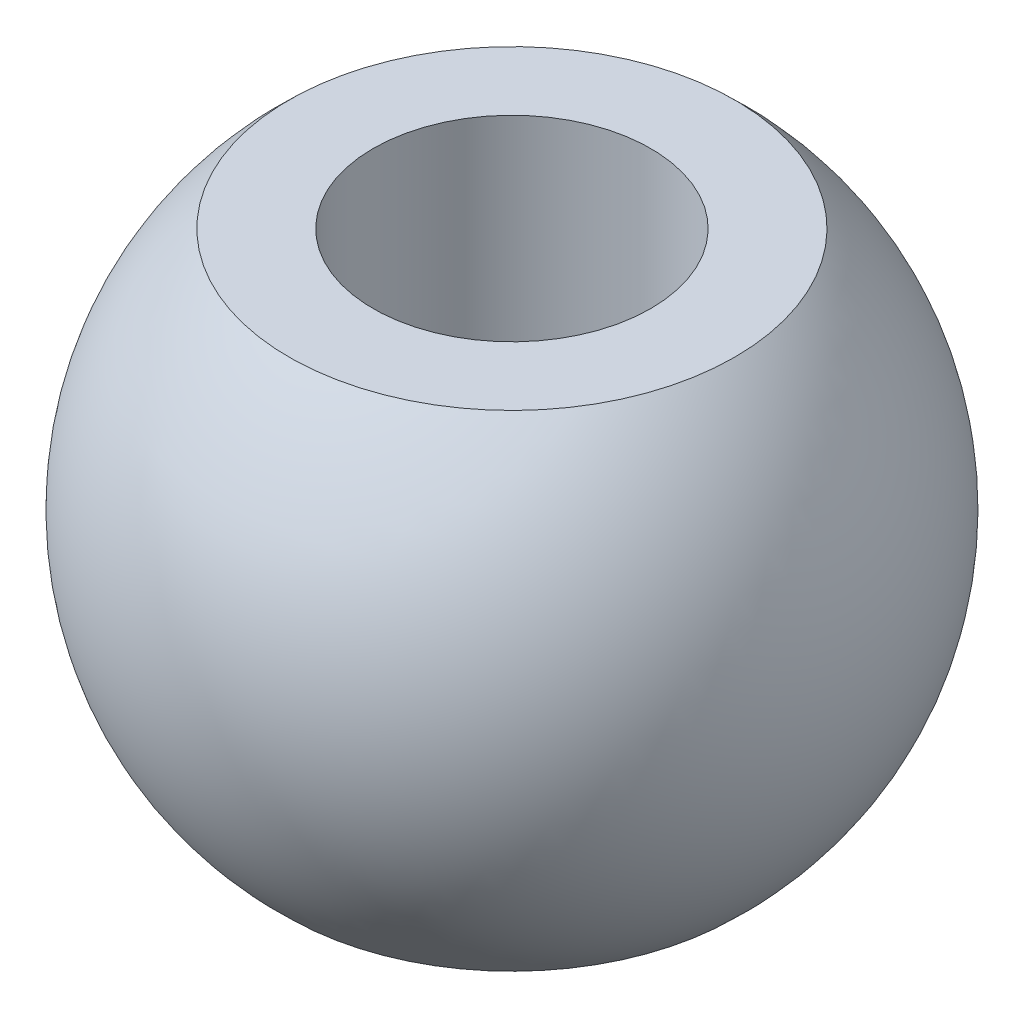
SolidWorks part; units mm, degrees
ref_plane "Спереди" through (0, 0, 0) normal (0, 0, 1) x (1, 0, 0)
ref_plane "Сверху" through (0, 0, 0) normal (0, 1, 0) x (1, 0, 0)
ref_plane "Справа" through (0, 0, 0) normal (1, 0, 0) x (0, 0, -1)
sketch "Эскиз3" plane through (0, 0, 0) normal (0, 0, 1) x (1, 0, 0)
  line L0 (0, 3.5) -> (0, 0) construction
  line L1 (2, 3.5) -> (2, -3.5)
  line L2 (2, 3.5) -> (3.2113, 3.5)
  line L3 (0, 0) -> (4.75, 0) construction
  line L4 (2, -3.5) -> (3.2113, -3.5)
  arc A0 (3.2113, -3.5) -> (3.2113, 3.5) centre (0, 0) ccw
  dimension "D1" = 4.75
  dimension "D2" = 2
  dimension "D3" = 3.5
revolve "Шарик" add sketch "Эскиз3" angle 360 about L0
